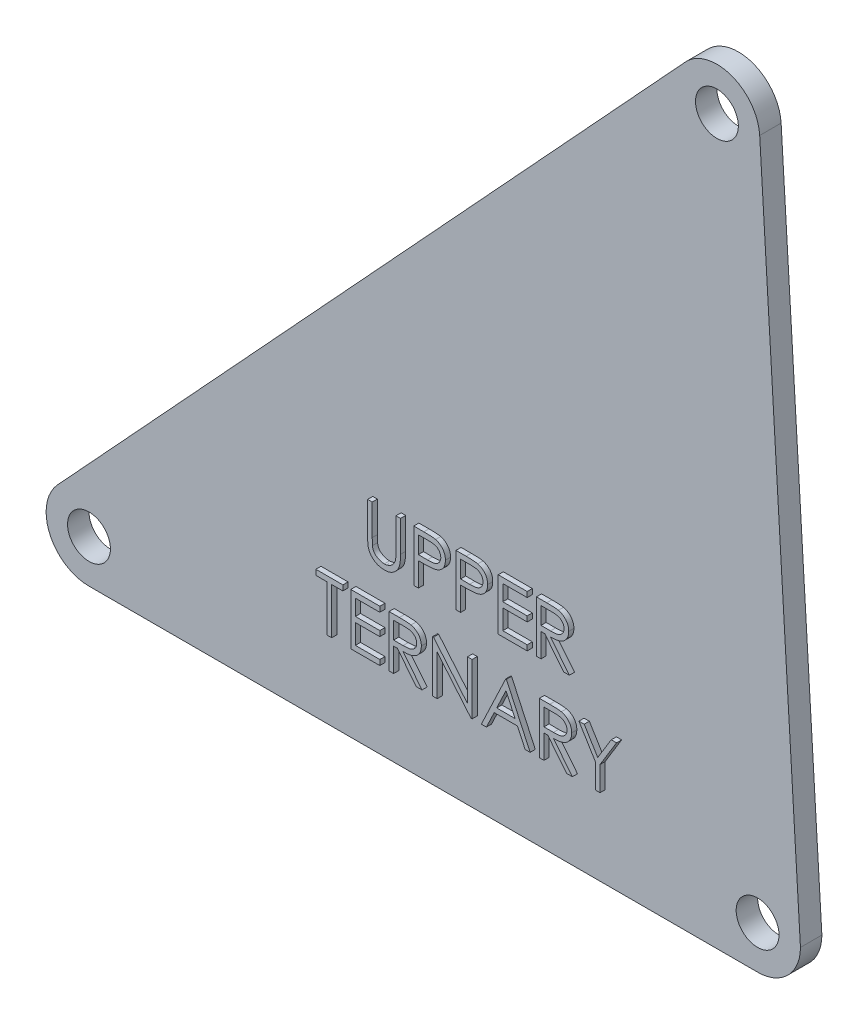
SolidWorks part; units mm, degrees
material "1060 Alloy"
ref_plane "Front Plane" through (0, 0, 0) normal (0, 0, 1) x (1, 0, 0)
ref_plane "Top Plane" through (0, 0, 0) normal (0, 1, 0) x (1, 0, 0)
ref_plane "Right Plane" through (0, 0, 0) normal (1, 0, 0) x (0, 0, -1)
sketch "Sketch1" plane through (0, 0, 0) normal (0, 0, 1) x (1, 0, 0)
  line L0 (0, 0) -> (-60.2639, 1007.8499) construction
  line L1 (-60.2639, 1007.8499) -> (-990.6, 0) construction
  line L2 (-990.6, 0) -> (0, 0) construction
  line L3 (-1037.7266, 42.5598) -> (-106.9238, 1050.9209)
  line L4 (-990.6, -63.5) -> (0, -63.5)
  line L5 (3.1233, 1011.633) -> (63.5, 0)
  circle A0 centre (-60.2639, 1007.8499) radius 31.75
  circle A1 centre (0, 0) radius 31.75
  circle A2 centre (-990.6, 0) radius 31.75
  arc A3 (3.1233, 1011.633) -> (-106.9238, 1050.9209) centre (-60.2639, 1007.8499) ccw
  arc A4 (0, -63.5) -> (63.0492, 7.5528) centre (0, 0) ccw
  arc A6 (-1037.7266, 42.5598) -> (-990.6, -63.5) centre (-990.6, 0) ccw
  dimension "D4" = 63.5
  dimension "D5" = 63.5
  dimension "D1" = 1009.65
  dimension "D2" = 990.6
  dimension "D3" = 1371.6
extrude "Boss-Extrude1" add sketch "Sketch1" along normal mid plane 31.75 contours L3 A6 L4 A4 L5 A3 A0 A1 A2
sketch "Sketch2" plane through (0, 0, 15.875) normal (0, 0, 1) x (1, 0, 0)
  line L0 (-699.8321, 185.6577) -> (-145.4928, 185.6577)
  text T0 "UPPER \r\nTERNARY" font "Century Schoolbook" height in points 16
sketch "Sketch4" plane through (0, 0, 15.875) normal (0, 0, 1) x (1, 0, 0)
  text T0 "UPPER\r\nTERNARY" font "Century Gothic" height 76.2
extrude "Boss-Extrude2" add sketch "Sketch4" along normal blind 7.62
sketch "Sketch5" plane through (0, 0, -15.875) normal (0, 0, -1) x (-1, 0, 0)
  text T0 "UPPER\r\nTERNARY" font "Century Schoolbook" height 76.2
extrude "Boss-Extrude3" add sketch "Sketch5" along normal blind 7.62
